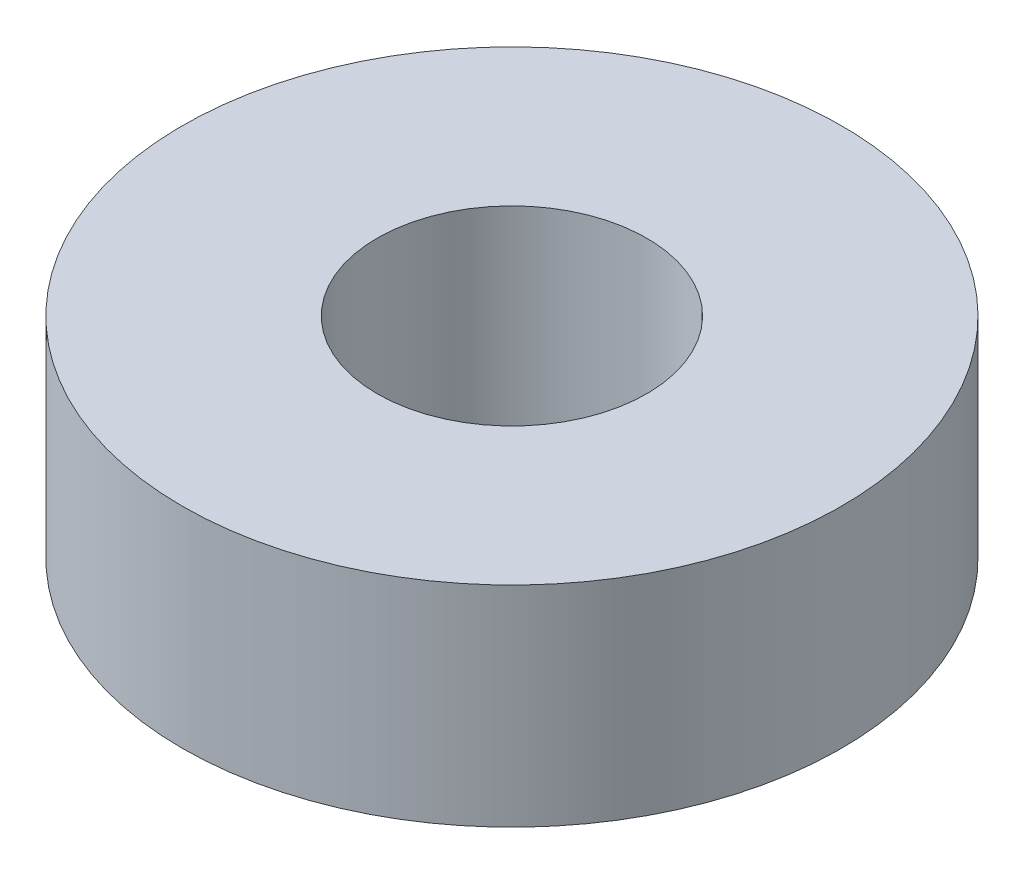
SolidWorks part; units mm, degrees
ref_plane "Alzado" through (0, 0, 0) normal (0, 0, 1) x (1, 0, 0)
ref_plane "Planta" through (0, 0, 0) normal (0, 1, 0) x (1, 0, 0)
ref_plane "Vista lateral" through (0, 0, 0) normal (1, 0, 0) x (0, 0, -1)
sketch "Croquis1" plane through (0, 0, 0) normal (0, 1, 0) x (1, 0, 0)
  circle A0 centre (0, 0) radius 11
  circle A1 centre (0, 0) radius 4.5
  dimension "D1" = 22
  dimension "D2" = 9
extrude "Saliente-Extruir1" add sketch "Croquis1" along normal blind 7
